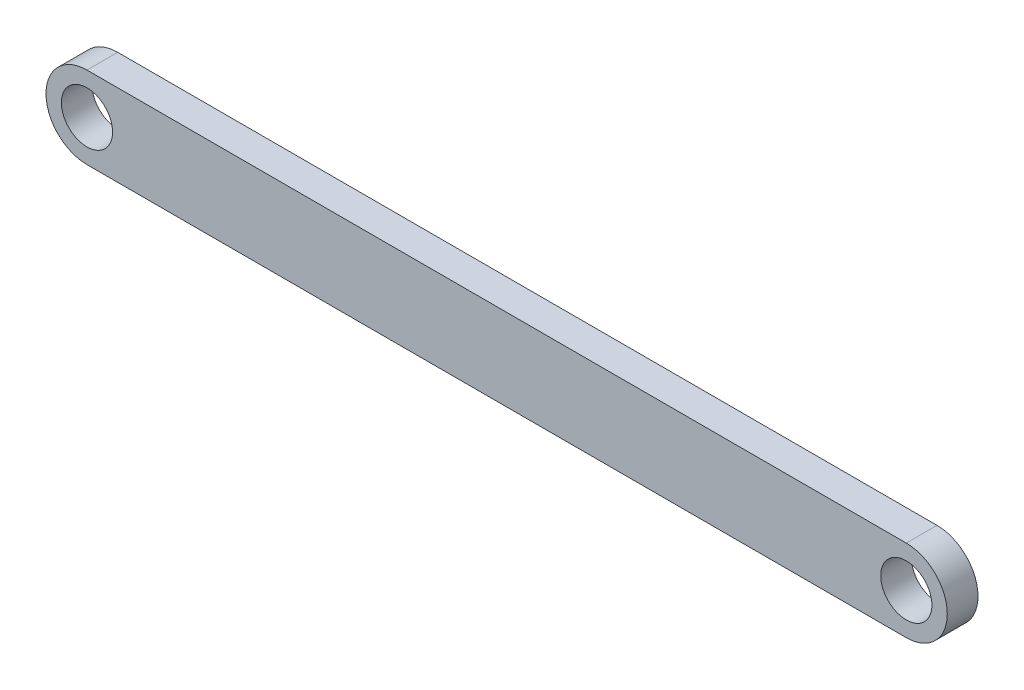
SolidWorks part; units mm, degrees
ref_plane "Front Plane" through (0, 0, 0) normal (0, 0, 1) x (1, 0, 0)
ref_plane "Top Plane" through (0, 0, 0) normal (0, 1, 0) x (1, 0, 0)
ref_plane "Right Plane" through (0, 0, 0) normal (1, 0, 0) x (0, 0, -1)
sketch "Sketch1" plane through (0, 0, 0) normal (0, 0, 1) x (1, 0, 0)
  line L1 (-40, -4) -> (40, -4)
  line L2 (-40, -4) -> (-40, 4)
  line L3 (-40, 4) -> (40, 4)
  line L4 (40, -4) -> (40, 4)
  line L5 (-40, -4) -> (40, 4) construction
  line L6 (-40, 4) -> (40, -4) construction
  circle A0 centre (-40, 0) radius 4
  circle A1 centre (40, 0) radius 4
  circle A2 centre (-40, 0) radius 2.5
  circle A3 centre (40, 0) radius 2.1669
  point P0 (0, 0)
  dimension "D3" = 5
  dimension "D4" = 4.3339
  dimension "D1" = 80
  dimension "D2" = 8
extrude "Boss-Extrude1" add sketch "Sketch1" along normal blind 3 contours L2 L1 L4 L3 | A0 | A1
sketch "Sketch2" plane through (0, 0, 3) normal (0, 0, 1) x (1, 0, 0)
  circle A0 centre (-40, 0) radius 2.5
  circle A1 centre (40, 0) radius 2.5
  dimension "D1" = 5
  dimension "D2" = 5
extrude "Cut-Extrude1" cut sketch "Sketch2" against normal up to surface (3 mm away) up to face at (0, 0, 0)
